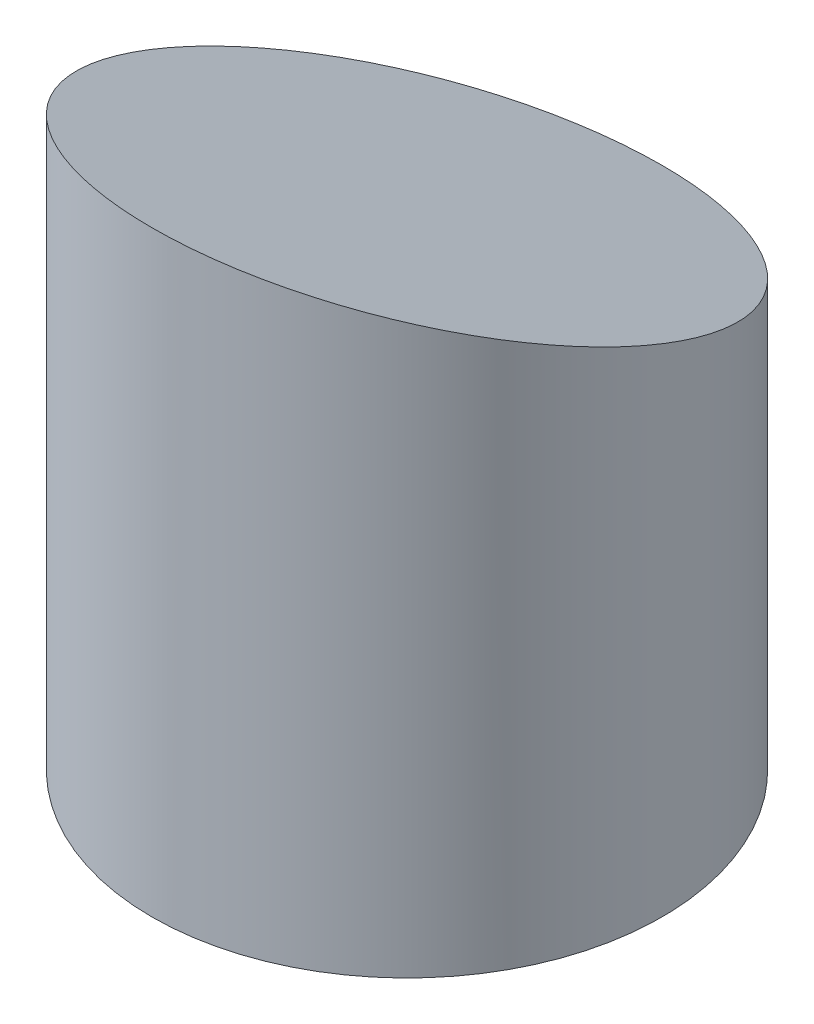
SolidWorks part; units mm, degrees
ref_plane "Front Plane" through (0, 0, 0) normal (0, 0, 1) x (1, 0, 0)
ref_plane "Top Plane" through (0, 0, 0) normal (0, 1, 0) x (1, 0, 0)
ref_plane "Right Plane" through (0, 0, 0) normal (1, 0, 0) x (0, 0, -1)
sketch "Sketch1" plane through (0, 0, 0) normal (0, 1, 0) x (1, 0, 0)
  circle A0 centre (0, 0) radius 52.55
  dimension "D1" = 105.1
extrude "Boss-Extrude1" add sketch "Sketch1" along normal blind 123
sketch "Sketch2" plane through (0, 0, 0) normal (1, 0, 0) x (0, 0, -1)
  line L0 (-52.55, 123) -> (52.55, 81.6)
  line L1 (52.55, 81.6) -> (52.55, 123)
  line L2 (52.55, 123) -> (-52.55, 123)
  dimension "D1" = 21.5
ref_plane "Plane1" through (0, 88.5587, -34.8842) normal (0, 0.9304, -0.3665) x (0, -0.3665, -0.9304)
sketch "Sketch3" plane through (0, 88.5587, -34.8842) normal (0, 0.9304, -0.3665) x (0, -0.3665, -0.9304)
  line L0 (-93.9731, 0) -> (18.9869, 0) construction
  circle A0 centre (-37.4931, 0) radius 54.5
  circle A1 centre (-37.4931, 0) radius 71.2801
  dimension "D1" = 109
  dimension "D2" = 142.5602
extrude "Cut-Extrude1" cut sketch "Sketch3" along normal through all contours A1 A0 | A0
sketch "Sketch4" plane through (0, 88.5587, -34.8842) normal (0, 0.9304, -0.3665) x (1, 0, 0)
  ellipse E1 centre (0, -37.4931) end of major axis (0, 18.9869) minor radius 52.55
  ellipse E2 centre (0, -37.4931) end of major axis (0, 18.9869) minor radius 52.55
  dimension "D1" = 0
